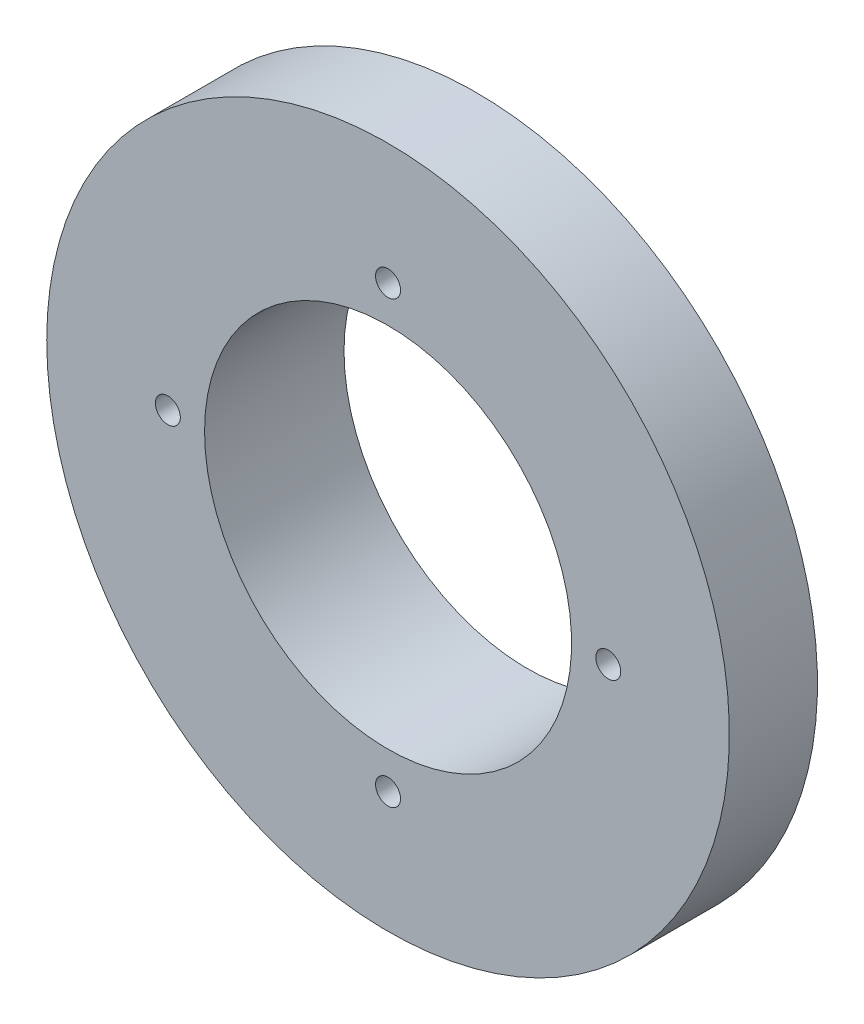
SolidWorks part; units mm, degrees
material "PLA"
ref_plane "Alzado" through (0, 0, 0) normal (0, 0, 1) x (1, 0, 0)
ref_plane "Planta" through (0, 0, 0) normal (0, 1, 0) x (1, 0, 0)
ref_plane "Vista lateral" through (0, 0, 0) normal (1, 0, 0) x (0, 0, -1)
sketch "Croquis2" plane through (0, 0, 0) normal (0, 1, 0) x (1, 0, 0)
  line L0 (25, -19) -> (25, 0)
  line L1 (25, 0) -> (35, 0)
  line L2 (35, 0) -> (35, -7)
  line L3 (35, -7) -> (46.5, -7)
  line L9 (0, 25.8442) -> (0, -26.689) construction
  line L10 (46.5, -19) -> (25, -19)
  line L11 (46.5, -7) -> (46.5, -19)
  dimension "D1" = 19
  dimension "D2" = 11.5
  dimension "D7" = 7
  dimension "D8" = 25
  dimension "D9" = 35
revolve "Revolución1" add sketch "Croquis2" angle 360 about L9
sketch "Sketch1" plane through (0, 0, 19) normal (0, 0, 1) x (1, 0, 0)
  circle A0 centre (0, 30) radius 1.7
  dimension "D2" = 3.4
  dimension "D1" = 30
extrude "Cut-Extrude1" cut sketch "Sketch1" against normal through all and the other way through all
pattern_circular "CirPattern1" count 4 over 360 about axis through (0, 0, 0) along (0, 0, 1) of "Cut-Extrude1"
